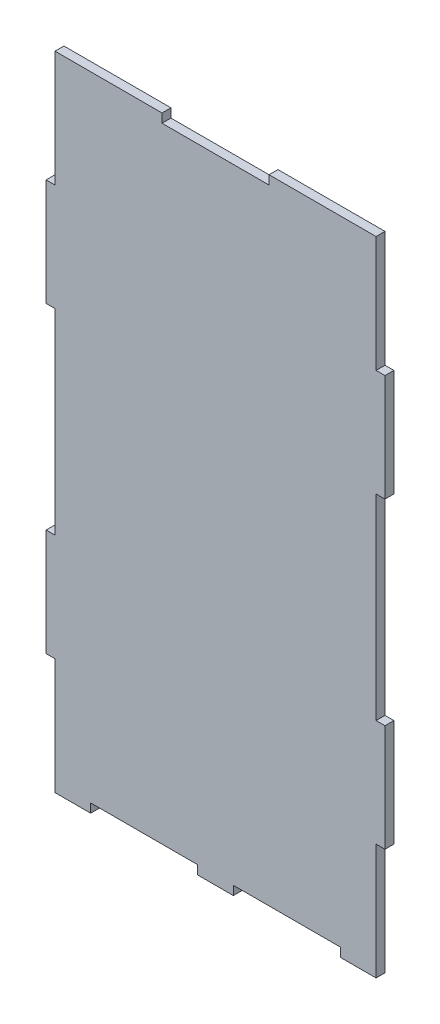
SolidWorks part; units mm, degrees
ref_plane "Front Plane" through (0, 0, 0) normal (0, 0, 1) x (1, 0, 0)
ref_plane "Top Plane" through (0, 0, 0) normal (0, 1, 0) x (1, 0, 0)
ref_plane "Right Plane" through (0, 0, 0) normal (1, 0, 0) x (0, 0, -1)
sketch "Sketch1" plane through (0, 0, 0) normal (0, 0, 1) x (1, 0, 0)
  line L1 (-192.6077, 179.9617) -> (35.9923, 179.9617)
  line L2 (-192.6077, 179.9617) -> (-192.6077, -277.2383)
  line L3 (-192.6077, -277.2383) -> (35.9923, -277.2383)
  line L4 (35.9923, 179.9617) -> (35.9923, -277.2383)
  dimension "D1" = 457.2
  dimension "D2" = 228.6
extrude "Boss-Extrude1" add sketch "Sketch1" along normal blind 6.35
sketch "Sketch2" plane through (0, 0, 6.35) normal (0, 0, 1) x (1, 0, 0)
  line L0 (-192.6077, 179.9617) -> (-192.6077, -277.2383) construction
  line L1 (-198.9577, 97.4117) -> (-192.6077, 97.4117)
  line L2 (-198.9577, 97.4117) -> (-198.9577, 21.2117)
  line L3 (-198.9577, 21.2117) -> (-192.6077, 21.2117)
  line L4 (-192.6077, 97.4117) -> (-192.6077, 21.2117)
  line L6 (-198.9577, -118.4883) -> (-192.6077, -118.4883)
  line L7 (-198.9577, -118.4883) -> (-198.9577, -194.6883)
  line L8 (-198.9577, -194.6883) -> (-192.6077, -194.6883)
  line L9 (-192.6077, -118.4883) -> (-192.6077, -194.6883)
  line L10 (-78.3077, 179.9617) -> (-78.3077, -277.2383) construction
  line L11 (35.9923, 179.9617) -> (-192.6077, 179.9617) construction
  line L12 (-192.6077, -277.2383) -> (35.9923, -277.2383) construction
  line L13 (42.3423, -194.6883) -> (35.9923, -194.6883)
  line L14 (42.3423, -118.4883) -> (42.3423, -194.6883)
  line L15 (35.9923, -118.4883) -> (35.9923, -194.6883)
  line L16 (42.3423, -118.4883) -> (35.9923, -118.4883)
  line L17 (42.3423, 21.2117) -> (35.9923, 21.2117)
  line L18 (42.3423, 97.4117) -> (42.3423, 21.2117)
  line L19 (35.9923, 97.4117) -> (35.9923, 21.2117)
  line L20 (42.3423, 97.4117) -> (35.9923, 97.4117)
  dimension "D1" = 82.55
  dimension "D2" = 76.2
  dimension "D4" = 82.55
  dimension "D5" = 6.35
extrude "Boss-Extrude4" add sketch "Sketch2" against normal through all
sketch "Sketch3" plane through (0, 0, 6.35) normal (0, 0, 1) x (1, 0, 0)
  line L0 (-192.6077, -277.2383) -> (35.9923, -277.2383) construction
  line L1 (-167.2077, -277.2383) -> (-91.0077, -277.2383)
  line L2 (-167.2077, -277.2383) -> (-167.2077, -270.8883)
  line L3 (-167.2077, -270.8883) -> (-91.0077, -270.8883)
  line L4 (-91.0077, -277.2383) -> (-91.0077, -270.8883)
  line L5 (-78.3077, 179.9617) -> (-78.3077, -277.2383) construction
  line L6 (35.9923, 179.9617) -> (-192.6077, 179.9617) construction
  line L7 (-65.6077, -277.2383) -> (-65.6077, -270.8883)
  line L8 (10.5923, -277.2383) -> (10.5923, -270.8883)
  line L9 (10.5923, -277.2383) -> (-65.6077, -277.2383)
  line L10 (10.5923, -270.8883) -> (-65.6077, -270.8883)
  line L11 (35.9923, 97.4117) -> (35.9923, 179.9617) construction
  line L12 (-116.4077, 179.9617) -> (-40.2077, 179.9617)
  line L13 (-116.4077, 179.9617) -> (-116.4077, 173.6117)
  line L14 (-116.4077, 173.6117) -> (-40.2077, 173.6117)
  line L15 (-40.2077, 179.9617) -> (-40.2077, 173.6117)
  dimension "D2" = 76.2
  dimension "D5" = 6.35
  dimension "D3" = 6.35
  dimension "D1" = 25.4
  dimension "D4" = 76.2
  dimension "D6" = 76.2
extrude "Cut-Extrude1" cut sketch "Sketch3" against normal blind 6.35
equation "\"width\"= 9in"
equation "\"Height\"= 18in"
equation "\"thick\"= 0.25"
equation "\"D1@Sketch1\"=\"Height\""
equation "\"D2@Sketch1\"=\"width\""
equation "\"D1@Boss-Extrude1\"=\"thick\""
equation "\"D5@Sketch2\"=\"thick\""
equation "\"D1\"= \"thick\""
equation "\"D3@Sketch3\"=\"thick\""
equation "\"D1@Cut-Extrude1\"=\"thick\""
equation "\"D5@Sketch3\"=\"thick\""
